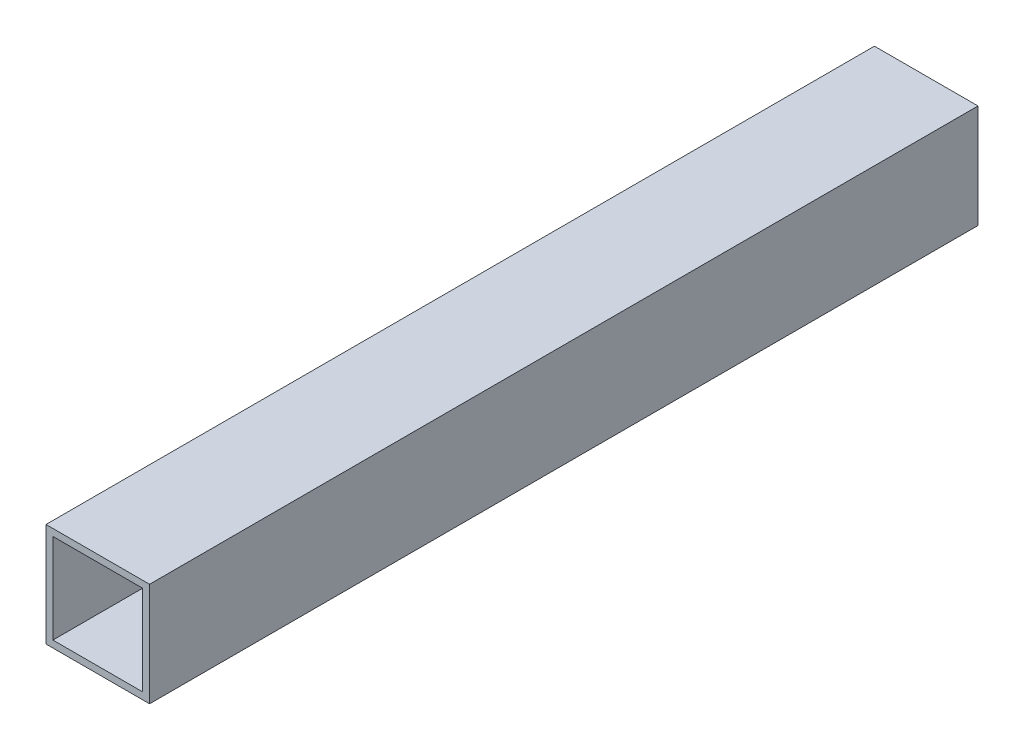
SolidWorks part; units mm, degrees
ref_plane "Front Plane" through (0, 0, 0) normal (0, 0, 1) x (1, 0, 0)
ref_plane "Top Plane" through (0, 0, 0) normal (0, 1, 0) x (1, 0, 0)
ref_plane "Right Plane" through (0, 0, 0) normal (1, 0, 0) x (0, 0, -1)
sketch "Sketch1" plane through (0, 0, 0) normal (0, 0, 1) x (1, 0, 0)
  line L0 (-13, 13) -> (13, 13)
  line L1 (-15, -15) -> (15, -15)
  line L2 (-15, -15) -> (-15, 15)
  line L3 (-15, 15) -> (15, 15)
  line L4 (15, -15) -> (15, 15)
  line L5 (-15, -15) -> (15, 15) construction
  line L6 (-15, 15) -> (15, -15) construction
  line L7 (13, -13) -> (13, 13)
  line L8 (-13, -13) -> (13, -13)
  line L9 (-13, -13) -> (-13, 13)
  point P0 (0, 0)
  dimension "D1" = 30
  dimension "D2" = 2
extrude "Boss-Extrude1" add sketch "Sketch1" along normal blind 240
